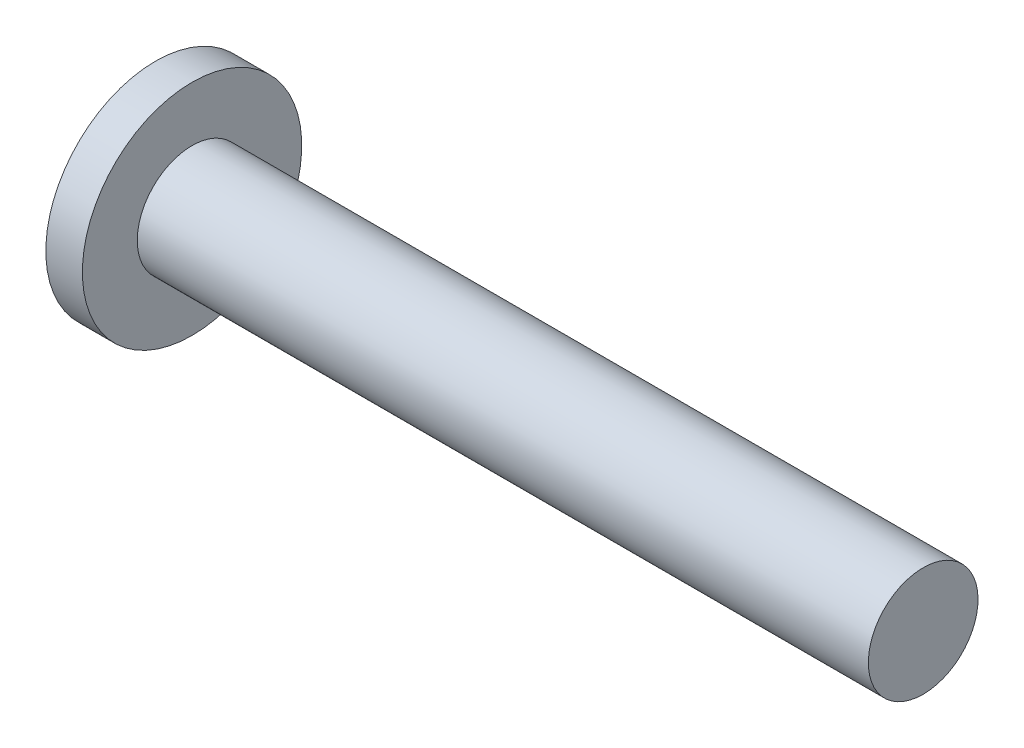
SolidWorks part; units mm, degrees
ref_plane "前视基准面" through (0, 0, 0) normal (0, 0, 1) x (1, 0, 0)
ref_plane "上视基准面" through (0, 0, 0) normal (0, 1, 0) x (1, 0, 0)
ref_plane "右视基准面" through (0, 0, 0) normal (1, 0, 0) x (0, 0, -1)
other "Configuration Table"
sketch "草图1" plane through (0, 0, 0) normal (0, 0, 1) x (1, 0, 0)
  line L0 (0, 0) -> (20, 0)
  line L1 (0, 0) -> (0, 1.5)
  line L2 (0, 1.5) -> (-1, 1.5)
  line L3 (20, 0) -> (20, -1.5)
  line L4 (20, -1.5) -> (18.7823, -1.5) construction
  line L5 (-1, 1.5) -> (-1, -1.5)
  line L6 (-1, -1.5) -> (20, -1.5)
  dimension "D1" = 20
  dimension "D2" = 1.5
  dimension "D3" = 1
  dimension "D4" = 1.5
revolve "旋转1" add sketch "草图1" angle 360 about L6
